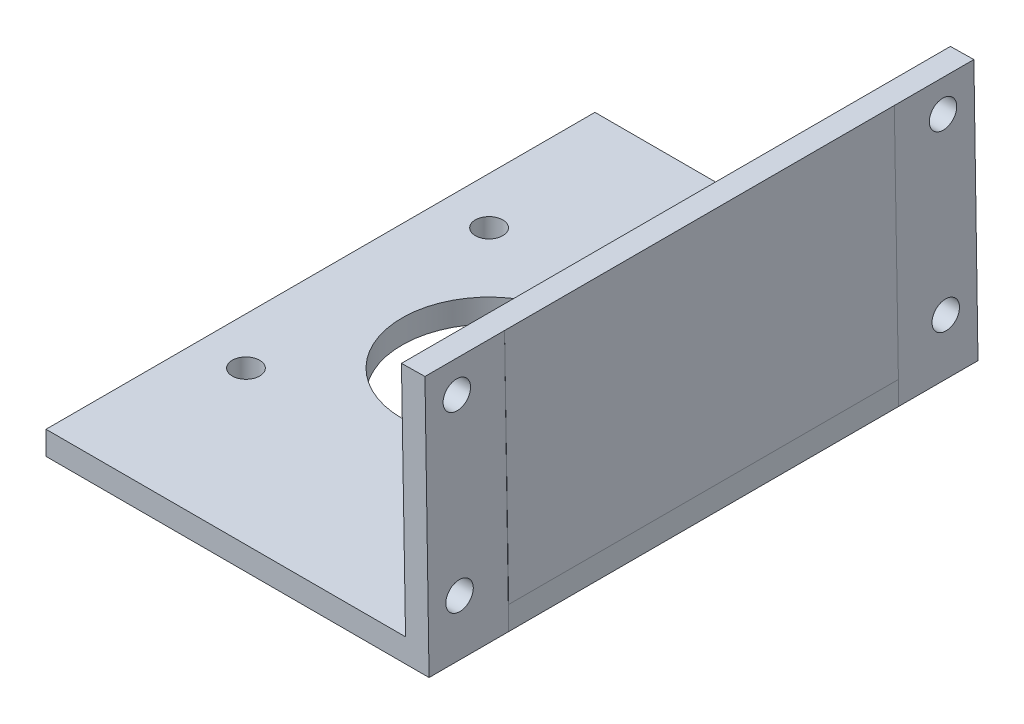
SolidWorks part; units mm, degrees
ref_plane "Plano frontal" through (0, 0, 0) normal (0, 0, 1) x (1, 0, 0)
ref_plane "Plano superior" through (0, 0, 0) normal (0, 1, 0) x (1, 0, 0)
ref_plane "Plano direito" through (0, 0, 0) normal (1, 0, 0) x (0, 0, -1)
sketch "Esboço1" plane through (0, 0, 0) normal (0, 1, 0) x (1, 0, 0)
  line L0 (0, 0) -> (0, 49.7)
  line L1 (0, 49.7) -> (42, 49.7)
  line L3 (0, 0) -> (42, 0)
  line L4 (42, 49.7) -> (44.85, 49.7)
  line L6 (42, 0) -> (44.85, 0)
  line L7 (44.85, 49.7) -> (45.85, 49.7)
  line L9 (45.85, 49.7) -> (48.85, 49.7)
  line L10 (48.85, 49.7) -> (48.85, 0)
  line L11 (44.85, 0) -> (48.85, 0)
  circle A0 centre (6, 9.35) radius 1.75
  circle A1 centre (37, 40.35) radius 1.75
  circle A2 centre (37, 9.35) radius 1.75
  circle A3 centre (6, 40.35) radius 1.75
extrude "Ressalto-extrusão1" add sketch "Esboço1" along normal blind 3
sketch "Esboço4" plane through (0, 0, 0) normal (0, 0, 1) x (1, 0, 0)
  line L0 (48.85, 3) -> (45.8505, 2.9476)
  line L1 (45.8505, 2.9476) -> (45.8246, 4.4287)
  line L2 (45.8246, 4.4287) -> (48.7121, 4.2533)
  line L3 (48.7121, 4.2533) -> (49.1124, 3.1012)
  line L4 (49.1124, 3.1012) -> (48.85, 3)
extrude "Corte-extrusão1" cut sketch "Esboço4" against normal through all
sketch "Esboço6" plane through (-0.0375, 2.1467, 0) normal (-0.0175, 0.9998, 0) x (0.9998, 0.0175, 0)
  line L0 (48.8949, 0) -> (45.8949, 0)
  line L1 (45.8949, 0) -> (45.8949, 49.7)
  line L2 (45.8949, 49.7) -> (48.8949, 49.7)
  line L3 (48.8949, 49.7) -> (48.8949, 0)
extrude "Ressalto-extrusão2" add sketch "Esboço6" along normal blind 30
sketch "Esboço9" plane through (0, 0, 0) normal (0, 0, 1) x (1, 0, 0)
  line L0 (45.3269, 32.9431) -> (48.3264, 32.9954)
  line L1 (48.3264, 32.9954) -> (48.85, 0)
  line L2 (48.85, 0) -> (0, 0)
  line L3 (0, 0) -> (0, 3)
  line L4 (0, 3) -> (45.8495, 3)
  line L5 (45.8495, 3) -> (45.3269, 32.9431)
  line L6 (45.3269, 32.9431) -> (48.3264, 32.9954)
  line M3 (48.3264, 32.9954) -> (45.3269, 32.9431)
  line M4 (45.3269, 32.9431) -> (45.8495, 3)
  line M5 (45.8495, 3) -> (0, 3)
  line M6 (0, 3) -> (0, 0)
  line M7 (0, 0) -> (48.85, 0)
extrude "Ressalto-extrusão5" add sketch "Esboço9" along normal blind 10.15 contours L1 M3 M4 M5 M6 M7
sketch "Esboço12" plane through (0, 0, -49.7) normal (0, 0, -1) x (-1, 0, 0)
  line L0 (0, 0) -> (-48.85, 0)
  line L1 (-48.85, 0) -> (-48.3264, 32.9954)
  line L2 (-48.3264, 32.9954) -> (-45.3269, 32.9431)
  line L3 (-45.3269, 32.9431) -> (-45.8495, 3)
  line L4 (-45.8495, 3) -> (0, 3)
  line L5 (0, 3) -> (0, 0)
extrude "Ressalto-extrusão6" add sketch "Esboço12" along normal blind 10.15 contours L5 L0 L1 L2 L3 L4
sketch "Esboço13" plane through (48.8875, 0.8533, 0) normal (0.9998, 0.0175, 0) x (0, 0, -1)
  circle A0 centre (-6.15, 28.147) radius 1.75
  circle A1 centre (-6.15, 6.147) radius 1.75
  circle A2 centre (55.85, 28.147) radius 1.75
  circle A3 centre (55.85, 6.147) radius 1.75
extrude "Corte-extrusão2" cut sketch "Esboço13" against normal through all
sketch "Esboço14" plane through (0, 3, 0) normal (0, 1, 0) x (1, 0, 0)
  line L0 (6, 40.35) -> (37, 40.35)
  line L1 (37, 40.35) -> (37, 9.35)
  line L2 (37, 9.35) -> (6, 9.35)
  line L3 (21.5, 24.85) -> (21.5, 9.35)
  line L4 (37, 24.85) -> (21.5, 24.85)
  circle A0 centre (21.5, 24.85) radius 11.1
extrude "Corte-extrusão3" cut sketch "Esboço14" against normal through all contours A0
